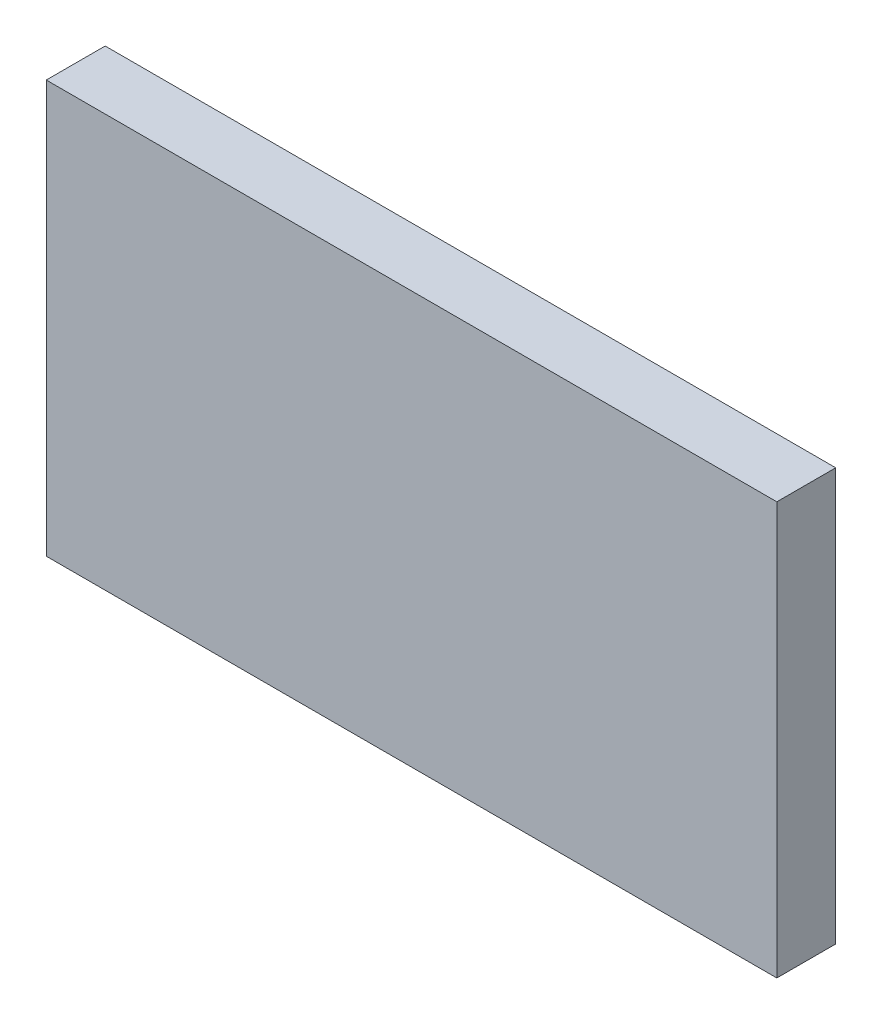
SolidWorks part; units mm, degrees
ref_plane "Plan de face" through (0, 0, 0) normal (0, 0, 1) x (1, 0, 0)
ref_plane "Plan de dessus" through (0, 0, 0) normal (0, 1, 0) x (1, 0, 0)
ref_plane "Plan de droite" through (0, 0, 0) normal (1, 0, 0) x (0, 0, -1)
sketch "Esquisse1" plane through (0, 0, 0) normal (0, 0, 1) x (1, 0, 0)
  line L1 (0, 0) -> (124, 0)
  line L2 (0, 0) -> (0, 70)
  line L3 (0, 70) -> (124, 70)
  line L4 (124, 0) -> (124, 70)
  dimension "D1" = 70
  dimension "D2" = 124
extrude "Boss.-Extru.1" add sketch "Esquisse1" along normal blind 10
